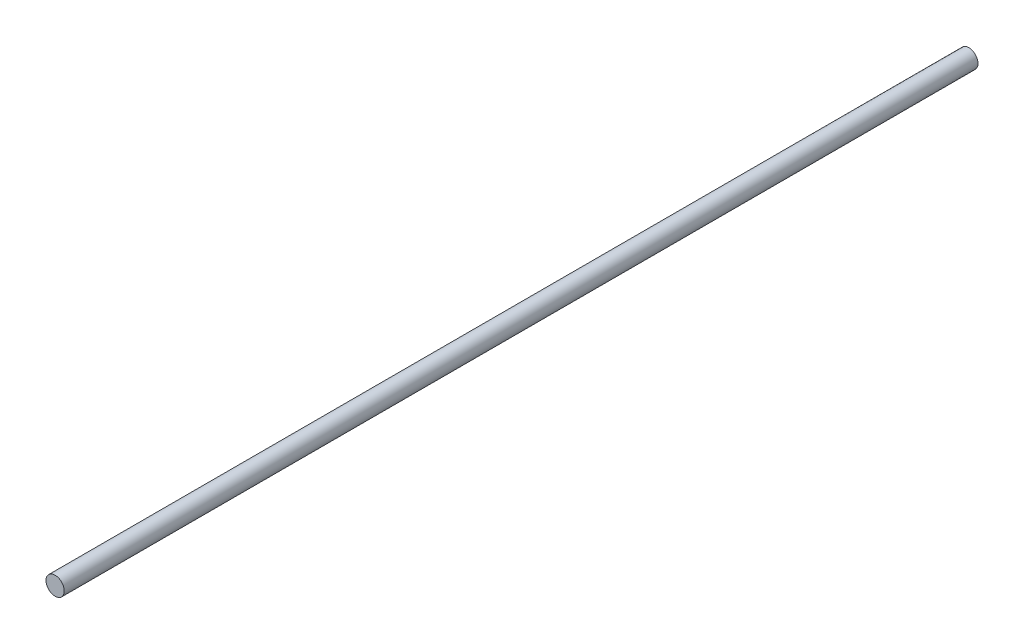
SolidWorks part; units mm, degrees
ref_plane "Front Plane" through (0, 0, 0) normal (0, 0, 1) x (1, 0, 0)
ref_plane "Top Plane" through (0, 0, 0) normal (0, 1, 0) x (1, 0, 0)
ref_plane "Right Plane" through (0, 0, 0) normal (1, 0, 0) x (0, 0, -1)
sketch "Sketch1" plane through (0, 0, 0) normal (0, 0, 1) x (1, 0, 0)
  circle A0 centre (-64.2616, 23.2129) radius 4
extrude "Boss-Extrude1" add sketch "Sketch1" along normal blind 400
